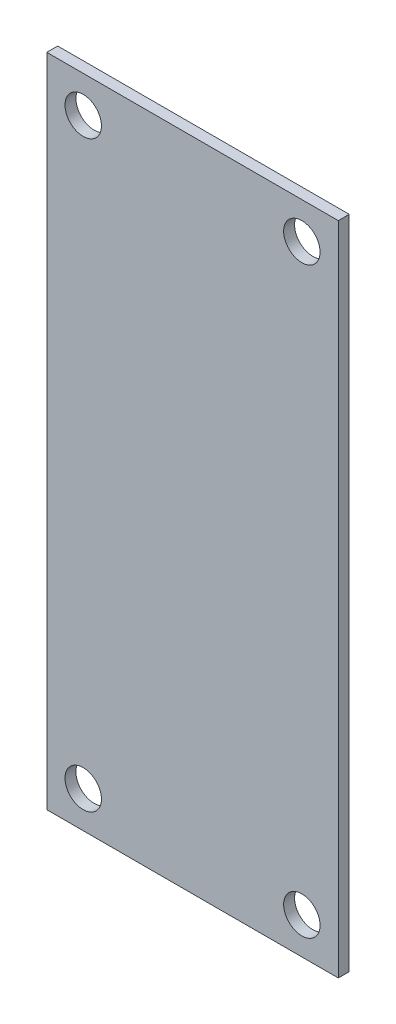
SolidWorks part; units mm, degrees
ref_plane "Front Plane" through (0, 0, 0) normal (0, 0, 1) x (1, 0, 0)
ref_plane "Top Plane" through (0, 0, 0) normal (0, 1, 0) x (1, 0, 0)
ref_plane "Right Plane" through (0, 0, 0) normal (1, 0, 0) x (0, 0, -1)
sketch "Sketch1" plane through (0, 0, 0) normal (0, 0, 1) x (1, 0, 0)
  line L1 (-10, 269) -> (10, 269)
  line L2 (-20, 261) -> (-20, 179)
  line L4 (20, 261) -> (20, 179)
  line L8 (-10, 269) -> (-20, 269)
  line L12 (-33.6325, 220) -> (60.8302, 220) construction
  line L13 (10, 269) -> (20, 269)
  line L24 (-20, 261) -> (-20, 269)
  line L26 (-20, 269) -> (20, 269)
  line L27 (-20, 269) -> (-20, 179)
  line L28 (-20, 179) -> (20, 179)
  line L29 (20, 269) -> (20, 179)
  dimension "D1" = 40
  dimension "D3" = 90
extrude "Boss-Extrude1" add sketch "Sketch1" along normal blind 1.5 contours L2 L12 L4 L29 L13 L1 L8 L24 | L12 L27 L28 L29
sketch "Sketch2" plane through (0, 0, 1.5) normal (0, 0, 1) x (1, 0, 0)
  line L0 (0, 269) -> (0, 179) construction
  line L1 (-20, 269) -> (20, 269) construction
  line L2 (-20, 179) -> (20, 179) construction
  line L3 (20, 224) -> (-20, 224) construction
  line L4 (20, 269) -> (20, 179) construction
  line L5 (-20, 269) -> (-20, 179) construction
  circle A0 centre (15, 264) radius 2.5
  circle A1 centre (15, 184) radius 2.5
  circle A2 centre (-15, 184) radius 2.5
  circle A3 centre (-15, 264) radius 2.5
  dimension "D1" = 5
  dimension "D2" = 5
  dimension "D3" = 5
extrude "Cut-Extrude1" cut sketch "Sketch2" against normal through all
